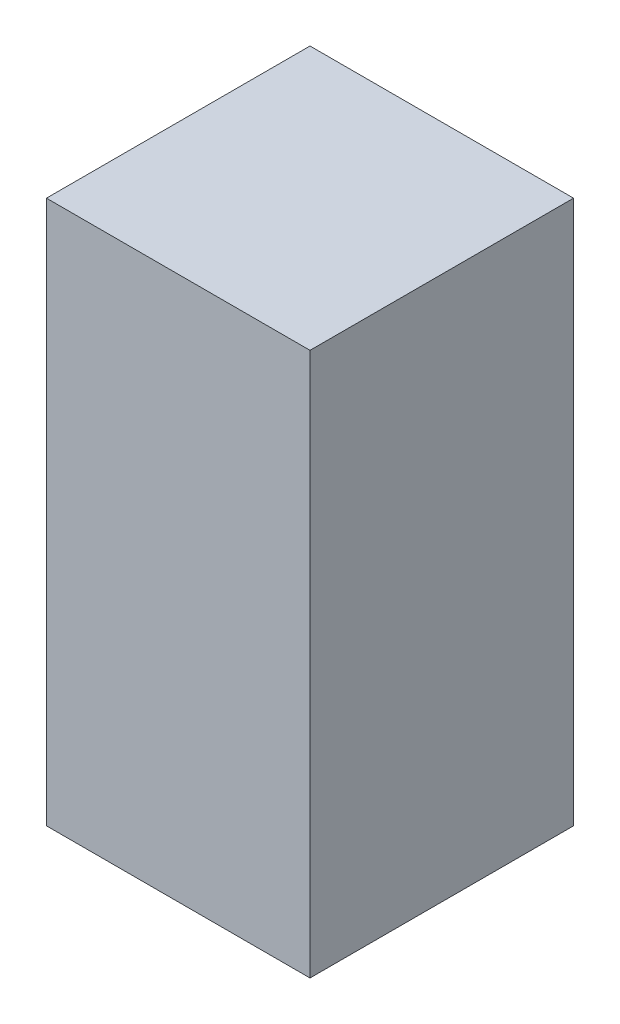
SolidWorks part; units mm, degrees
material "6061 Alloy"
ref_plane "Front Plane" through (0, 0, 0) normal (0, 0, 1) x (1, 0, 0)
ref_plane "Top Plane" through (0, 0, 0) normal (0, 1, 0) x (1, 0, 0)
ref_plane "Right Plane" through (0, 0, 0) normal (1, 0, 0) x (0, 0, -1)
sketch "Sketch1" plane through (0, 0, 0) normal (0, 1, 0) x (1, 0, 0)
  line L1 (0, 0) -> (168.275, 0)
  line L2 (0, 0) -> (0, -168.275)
  line L3 (0, -168.275) -> (168.275, -168.275)
  line L4 (168.275, 0) -> (168.275, -168.275)
  dimension "D1" = 168.275
extrude "Boss-Extrude1" add sketch "Sketch1" along normal blind 347.0758
